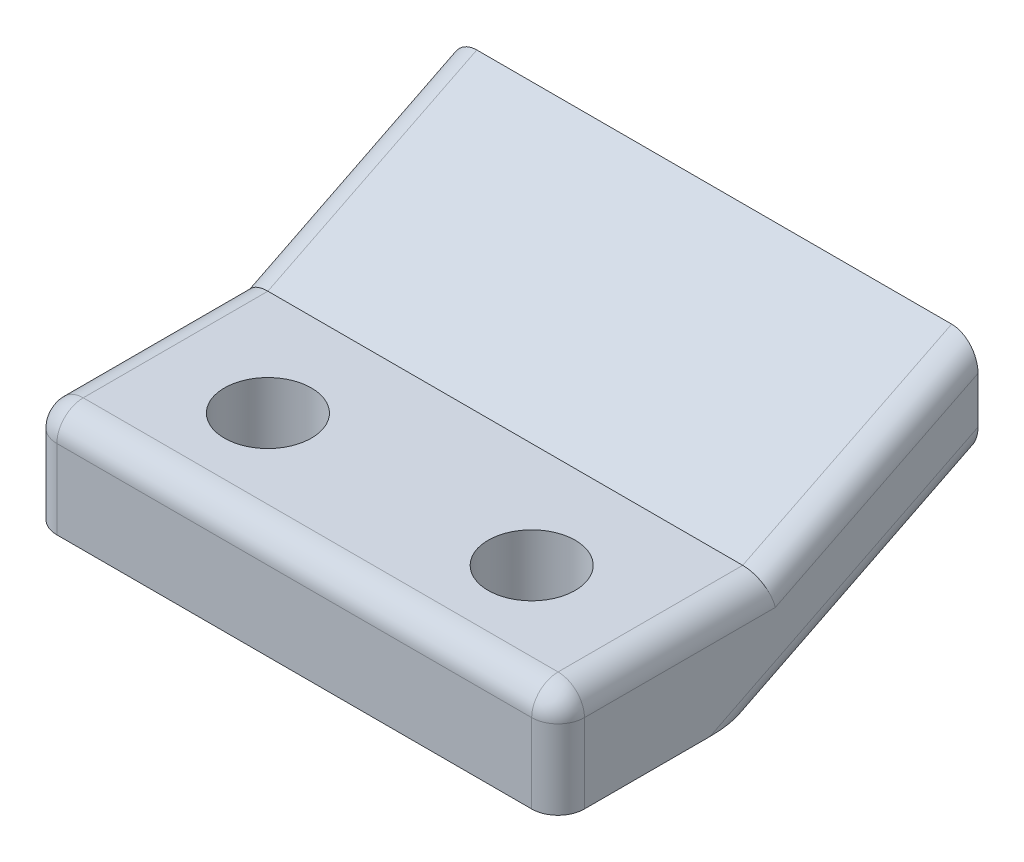
SolidWorks part; units mm, degrees
ref_plane "Plano frontal" through (0, 0, 0) normal (0, 0, 1) x (1, 0, 0)
ref_plane "Plano superior" through (0, 0, 0) normal (0, 1, 0) x (1, 0, 0)
ref_plane "Plano direito" through (0, 0, 0) normal (1, 0, 0) x (0, 0, -1)
sketch "Esboço4" plane through (0, 0, 0) normal (1, 0, 0) x (0, 0, -1)
  line L0 (0, 0) -> (15.92, 7.96)
  line L1 (15.92, 7.96) -> (15.92, 3.96)
  line L2 (15.92, 3.96) -> (8, 0)
  line L3 (8, 0) -> (0, 0)
  point P3 (0, 0)
  point P6 (0, 0)
  dimension "D1" = 15.92
  dimension "D2" = 4
  dimension "D3" = 8
extrude "Ressalto-extrusão2" add sketch "Esboço4" along normal blind 20
sketch "Esboço5" plane through (0, 0, 0) normal (0, -1, 0) x (1, 0, 0)
  line L0 (20, 0) -> (0, 0) construction
  line L1 (20, 0) -> (20, -8) construction
  line L2 (0, 0) -> (0, -8) construction
  circle A0 centre (5, -4) radius 1.65
  circle A1 centre (15, -4) radius 1.65
  point P0 (5, -4)
  point P1 (15, -4)
  dimension "D3" = 5
  dimension "D4" = 5
  dimension "D5" = 3.3
  dimension "D6" = 3.3
  dimension "D1" = 4
  dimension "D2" = 4
sketch "Esboço6" plane through (0, 0, 0) normal (0, -1, 0) x (1, 0, 0)
  line L1 (0, 0) -> (20, 0)
  line L2 (0, 0) -> (0, -8)
  line L3 (0, -8) -> (20, -8)
  line L4 (20, 0) -> (20, -8)
extrude "Ressalto-extrusão3" add sketch "Esboço6" against normal blind 4
extrude "Corte-extrusão2" cut sketch "Esboço5" against normal through all
fillet "Filete1" radius 1 9 edges at (20, 1.98, -11.96) (0, 1.98, -11.96) (20, 5.98, -11.96) (0, 5.98, -11.96) (20, 4, -4) (0, 4, -4) (20, 2, 0) (0, 2, 0) (10, 4, 0)
